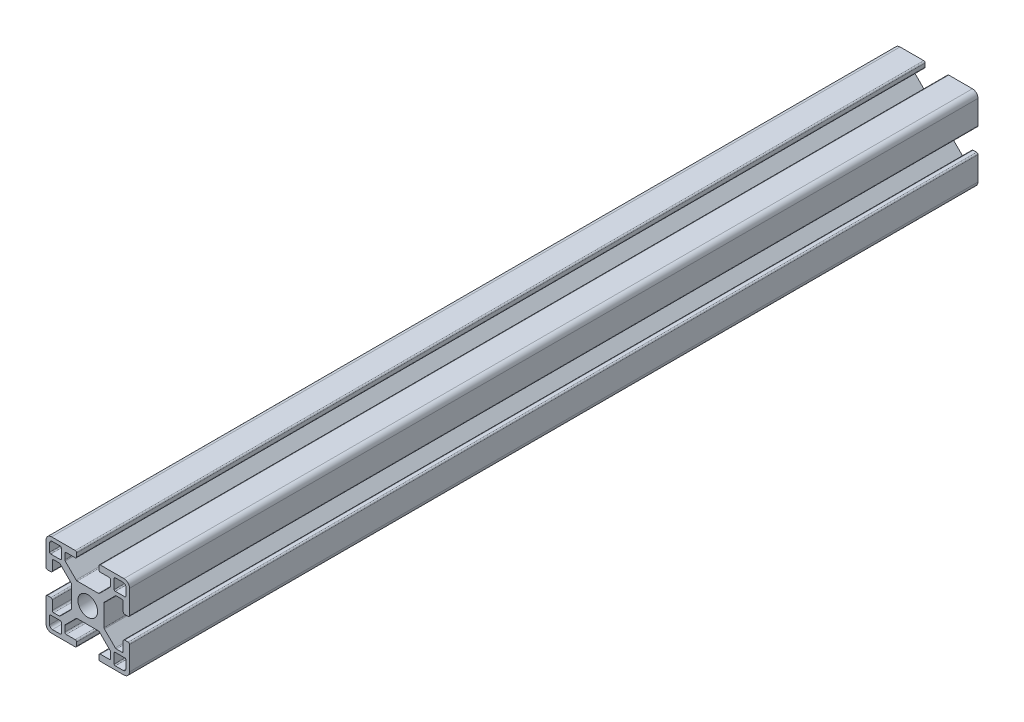
SolidWorks part; units mm, degrees
ref_plane "Front Plane" through (0, 0, 0) normal (0, 0, 1) x (1, 0, 0)
ref_plane "Top Plane" through (0, 0, 0) normal (0, 1, 0) x (1, 0, 0)
ref_plane "Right Plane" through (0, 0, 0) normal (1, 0, 0) x (0, 0, -1)
sketch "Sketch1" plane through (0, 0, 0) normal (0, 0, 1) x (1, 0, 0)
  line L0 (3.9799, -2.4733) -> (3.1981, -1.4942) construction
  line L1 (1.4942, -3.1981) -> (2.4733, -3.9799) construction
  line L2 (-2.4733, -3.9799) -> (-1.4942, -3.1981) construction
  line L3 (-3.1981, -1.4942) -> (-3.9799, -2.4733) construction
  line L4 (-3.9799, 2.4733) -> (-3.1981, 1.4942) construction
  line L5 (-1.4942, 3.1981) -> (-2.4733, 3.9799) construction
  line L6 (2.4733, 3.9799) -> (1.4942, 3.1981) construction
  line L7 (3.1981, 1.4942) -> (3.9799, 2.4733) construction
  line L8 (-12.6999, -13.6999) -> (-9.881, -13.6999)
  line L9 (-13.6999, -9.881) -> (-13.6999, -12.6999)
  line L10 (-9.88, -9.5) -> (-13.3189, -9.5)
  line L11 (-9.5, -13.3189) -> (-9.5, -9.88)
  line L12 (13.6999, -12.6999) -> (13.6999, -9.881)
  line L13 (9.881, -13.6999) -> (12.6999, -13.6999)
  line L14 (9.5, -9.88) -> (9.5, -13.3189)
  line L15 (13.3189, -9.5) -> (9.88, -9.5)
  line L16 (9.88, 9.5) -> (13.3189, 9.5)
  line L17 (9.5, 13.3189) -> (9.5, 9.88)
  line L18 (12.6999, 13.6999) -> (9.881, 13.6999)
  line L19 (13.6999, 9.881) -> (13.6999, 12.6999)
  line L20 (-13.6999, 12.6999) -> (-13.6999, 9.881)
  line L21 (-9.881, 13.6999) -> (-12.6999, 13.6999)
  line L22 (-9.5, 9.88) -> (-9.5, 13.3189)
  line L23 (-13.3189, 9.5) -> (-9.88, 9.5)
  line L24 (14.4999, -4) -> (13.2425, -4)
  line L25 (12.7425, -4.5) -> (12.7425, -7.7325)
  line L26 (12.2428, -8.25) -> (10.2602, -8.25)
  line L27 (9.9066, -8.1035) -> (5.9811, -4.178)
  line L28 (5.8347, -3.8245) -> (5.8347, -1.0125)
  line L29 (5.8347, -1.0125) -> (5.3247, -0.0625) construction
  line L30 (5.3247, -0.0625) -> (5.8347, 0.8875) construction
  line L31 (5.8347, 0.8875) -> (5.8347, 3.8245)
  line L32 (5.9811, 4.178) -> (9.9066, 8.1035)
  line L33 (10.2602, 8.25) -> (12.2428, 8.25)
  line L34 (12.7425, 7.7325) -> (12.7425, 4.5)
  line L35 (13.2425, 4) -> (14.4999, 4)
  line L36 (14.9999, 4.5) -> (14.9999, 12.9999)
  line L37 (12.9999, 14.9999) -> (4.5, 14.9999)
  line L38 (4, 14.4999) -> (4, 13.2425)
  line L39 (4.5, 12.7425) -> (7.7325, 12.7425)
  line L40 (8.25, 12.2428) -> (8.25, 10.2602)
  line L41 (8.1035, 9.9066) -> (4.178, 5.9811)
  line L42 (3.8245, 5.8347) -> (0.95, 5.8347)
  line L43 (0.95, 5.8347) -> (0, 5.3247) construction
  line L44 (0, 5.3247) -> (-0.95, 5.8347) construction
  line L45 (-0.95, 5.8347) -> (-3.8245, 5.8347)
  line L46 (-4.178, 5.9811) -> (-8.1035, 9.9066)
  line L47 (-8.25, 10.2602) -> (-8.25, 12.2428)
  line L48 (-7.7325, 12.7425) -> (-4.5, 12.7425)
  line L49 (-4, 13.2425) -> (-4, 14.4999)
  line L50 (-4.5, 14.9999) -> (-12.9999, 14.9999)
  line L51 (-14.9999, 12.9999) -> (-14.9999, 4.5)
  line L52 (-14.4999, 4) -> (-13.2425, 4)
  line L53 (-12.7425, 4.5) -> (-12.7425, 7.7325)
  line L54 (-12.2428, 8.25) -> (-10.2602, 8.25)
  line L55 (-9.9066, 8.1035) -> (-5.9811, 4.178)
  line L56 (-5.8347, 3.8245) -> (-5.8347, 0.8875)
  line L57 (-5.8347, 0.8875) -> (-5.3247, -0.0625) construction
  line L58 (-5.3247, -0.0625) -> (-5.8347, -1.0125) construction
  line L59 (-5.8347, -1.0125) -> (-5.8347, -3.8245)
  line L60 (-5.9811, -4.178) -> (-9.9066, -8.1035)
  line L61 (-10.2602, -8.25) -> (-12.2428, -8.25)
  line L62 (-12.7425, -7.7325) -> (-12.7425, -4.5)
  line L63 (-13.2425, -4) -> (-14.4999, -4)
  line L64 (-14.9999, -4.5) -> (-14.9999, -12.9999)
  line L65 (-12.9999, -14.9999) -> (-4.5, -14.9999)
  line L66 (-4, -14.4999) -> (-4, -13.2425)
  line L67 (-4.5, -12.7425) -> (-7.7325, -12.7425)
  line L68 (-8.25, -12.2428) -> (-8.25, -10.2602)
  line L69 (-8.1035, -9.9066) -> (-4.178, -5.9811)
  line L70 (-3.8245, -5.8347) -> (-0.95, -5.8347)
  line L71 (-0.95, -5.8347) -> (0, -5.3247) construction
  line L72 (0, -5.3247) -> (0.95, -5.8347) construction
  line L73 (0.95, -5.8347) -> (3.8245, -5.8347)
  line L74 (4.178, -5.9811) -> (8.1035, -9.9066)
  line L75 (8.25, -10.2602) -> (8.25, -12.2428)
  line L76 (7.7325, -12.7425) -> (4.5, -12.7425)
  line L77 (4, -13.2425) -> (4, -14.4999)
  line L78 (4.5, -14.9999) -> (12.9999, -14.9999)
  line L79 (14.9999, -12.9999) -> (14.9999, -4.5)
  line L80 (-5.8347, -1.0125) -> (-5.8347, 0.8875)
  line L81 (-0.95, 5.8347) -> (0.95, 5.8347)
  line L82 (5.8347, 0.8875) -> (5.8347, -1.0125)
  line L83 (-0.95, -5.8347) -> (0.95, -5.8347)
  arc A0 (2.4733, -3.9799) -> (3.9799, -2.4733) centre (3.1422, -3.1422) ccw construction
  arc A1 (-1.4942, -3.1981) -> (1.4942, -3.1981) centre (0, 0) ccw construction
  arc A2 (-3.9799, -2.4733) -> (-2.4733, -3.9799) centre (-3.1422, -3.1422) ccw construction
  arc A3 (-3.1981, 1.4942) -> (-3.1981, -1.4942) centre (0, 0) ccw construction
  arc A4 (-2.4733, 3.9799) -> (-3.9799, 2.4733) centre (-3.1422, 3.1422) ccw construction
  arc A5 (1.4942, 3.1981) -> (-1.4942, 3.1981) centre (0, 0) ccw construction
  arc A6 (3.9799, 2.4733) -> (2.4733, 3.9799) centre (3.1422, 3.1422) ccw construction
  arc A7 (3.1981, -1.4942) -> (3.1981, 1.4942) centre (0, 0) ccw construction
  arc A8 (-13.6999, -12.6999) -> (-12.6999, -13.6999) centre (-12.6999, -12.6999) ccw
  arc A9 (-13.3189, -9.5) -> (-13.6999, -9.881) centre (-13.3189, -9.881) ccw
  arc A10 (-9.5, -9.88) -> (-9.88, -9.5) centre (-9.88, -9.88) ccw
  arc A11 (-9.881, -13.6999) -> (-9.5, -13.3189) centre (-9.881, -13.3189) ccw
  arc A12 (12.6999, -13.6999) -> (13.6999, -12.6999) centre (12.6999, -12.6999) ccw
  arc A13 (9.5, -13.3189) -> (9.881, -13.6999) centre (9.881, -13.3189) ccw
  arc A14 (9.88, -9.5) -> (9.5, -9.88) centre (9.88, -9.88) ccw
  arc A15 (13.6999, -9.881) -> (13.3189, -9.5) centre (13.3189, -9.881) ccw
  arc A16 (9.5, 9.88) -> (9.88, 9.5) centre (9.88, 9.88) ccw
  arc A17 (9.881, 13.6999) -> (9.5, 13.3189) centre (9.881, 13.3189) ccw
  arc A18 (13.6999, 12.6999) -> (12.6999, 13.6999) centre (12.6999, 12.6999) ccw
  arc A19 (13.3189, 9.5) -> (13.6999, 9.881) centre (13.3189, 9.881) ccw
  arc A20 (14.9999, -4.5) -> (14.4999, -4) centre (14.4999, -4.5) ccw
  arc A21 (13.2425, -4) -> (12.7425, -4.5) centre (13.2425, -4.5) ccw
  arc A22 (12.2428, -8.25) -> (12.7425, -7.7325) centre (12.2428, -7.75) ccw
  arc A23 (9.9066, -8.1035) -> (10.2602, -8.25) centre (10.2602, -7.75) ccw
  arc A24 (5.8347, -3.8245) -> (5.9811, -4.178) centre (6.3347, -3.8245) ccw
  arc A25 (5.9811, 4.178) -> (5.8347, 3.8245) centre (6.3347, 3.8245) ccw
  arc A26 (10.2602, 8.25) -> (9.9066, 8.1035) centre (10.2602, 7.75) ccw
  arc A27 (12.7425, 7.7325) -> (12.2428, 8.25) centre (12.2428, 7.75) ccw
  arc A28 (12.7425, 4.5) -> (13.2425, 4) centre (13.2425, 4.5) ccw
  arc A29 (14.4999, 4) -> (14.9999, 4.5) centre (14.4999, 4.5) ccw
  arc A30 (14.9999, 12.9999) -> (12.9999, 14.9999) centre (12.9999, 12.9999) ccw
  arc A31 (4.5, 14.9999) -> (4, 14.4999) centre (4.5, 14.4999) ccw
  arc A32 (4, 13.2425) -> (4.5, 12.7425) centre (4.5, 13.2425) ccw
  arc A33 (8.25, 12.2428) -> (7.7325, 12.7425) centre (7.75, 12.2428) ccw
  arc A34 (8.1035, 9.9066) -> (8.25, 10.2602) centre (7.75, 10.2602) ccw
  arc A35 (3.8245, 5.8347) -> (4.178, 5.9811) centre (3.8245, 6.3347) ccw
  arc A36 (-4.178, 5.9811) -> (-3.8245, 5.8347) centre (-3.8245, 6.3347) ccw
  arc A37 (-8.25, 10.2602) -> (-8.1035, 9.9066) centre (-7.75, 10.2602) ccw
  arc A38 (-7.7325, 12.7425) -> (-8.25, 12.2428) centre (-7.75, 12.2428) ccw
  arc A39 (-4.5, 12.7425) -> (-4, 13.2425) centre (-4.5, 13.2425) ccw
  arc A40 (-4, 14.4999) -> (-4.5, 14.9999) centre (-4.5, 14.4999) ccw
  arc A41 (-12.9999, 14.9999) -> (-14.9999, 12.9999) centre (-12.9999, 12.9999) ccw
  arc A42 (-14.9999, 4.5) -> (-14.4999, 4) centre (-14.4999, 4.5) ccw
  arc A43 (-13.2425, 4) -> (-12.7425, 4.5) centre (-13.2425, 4.5) ccw
  arc A44 (-12.2428, 8.25) -> (-12.7425, 7.7325) centre (-12.2428, 7.75) ccw
  arc A45 (-9.9066, 8.1035) -> (-10.2602, 8.25) centre (-10.2602, 7.75) ccw
  arc A46 (-5.8347, 3.8245) -> (-5.9811, 4.178) centre (-6.3347, 3.8245) ccw
  arc A47 (-5.9811, -4.178) -> (-5.8347, -3.8245) centre (-6.3347, -3.8245) ccw
  arc A48 (-10.2602, -8.25) -> (-9.9066, -8.1035) centre (-10.2602, -7.75) ccw
  arc A49 (-12.7425, -7.7325) -> (-12.2428, -8.25) centre (-12.2428, -7.75) ccw
  arc A50 (-12.7425, -4.5) -> (-13.2425, -4) centre (-13.2425, -4.5) ccw
  arc A51 (-14.4999, -4) -> (-14.9999, -4.5) centre (-14.4999, -4.5) ccw
  arc A52 (-14.9999, -12.9999) -> (-12.9999, -14.9999) centre (-12.9999, -12.9999) ccw
  arc A53 (-4.5, -14.9999) -> (-4, -14.4999) centre (-4.5, -14.4999) ccw
  arc A54 (-4, -13.2425) -> (-4.5, -12.7425) centre (-4.5, -13.2425) ccw
  arc A55 (-8.25, -12.2428) -> (-7.7325, -12.7425) centre (-7.75, -12.2428) ccw
  arc A56 (-8.1035, -9.9066) -> (-8.25, -10.2602) centre (-7.75, -10.2602) ccw
  arc A57 (-3.8245, -5.8347) -> (-4.178, -5.9811) centre (-3.8245, -6.3347) ccw
  arc A58 (4.178, -5.9811) -> (3.8245, -5.8347) centre (3.8245, -6.3347) ccw
  arc A59 (8.25, -10.2602) -> (8.1035, -9.9066) centre (7.75, -10.2602) ccw
  arc A60 (7.7325, -12.7425) -> (8.25, -12.2428) centre (7.75, -12.2428) ccw
  arc A61 (4.5, -12.7425) -> (4, -13.2425) centre (4.5, -13.2425) ccw
  arc A62 (4, -14.4999) -> (4.5, -14.9999) centre (4.5, -14.4999) ccw
  arc A63 (12.9999, -14.9999) -> (14.9999, -12.9999) centre (12.9999, -12.9999) ccw
  arc A64 (-12.6999, 13.6999) -> (-13.6999, 12.6999) centre (-12.6999, 12.6999) ccw
  arc A65 (-9.5, 13.3189) -> (-9.881, 13.6999) centre (-9.881, 13.3189) ccw
  arc A66 (-9.88, 9.5) -> (-9.5, 9.88) centre (-9.88, 9.88) ccw
  arc A67 (-13.6999, 9.881) -> (-13.3189, 9.5) centre (-13.3189, 9.881) ccw
  circle A68 centre (0, 0) radius 3.53
extrude "Boss-Extrude1" add sketch "Sketch1" along normal mid plane 304.8
